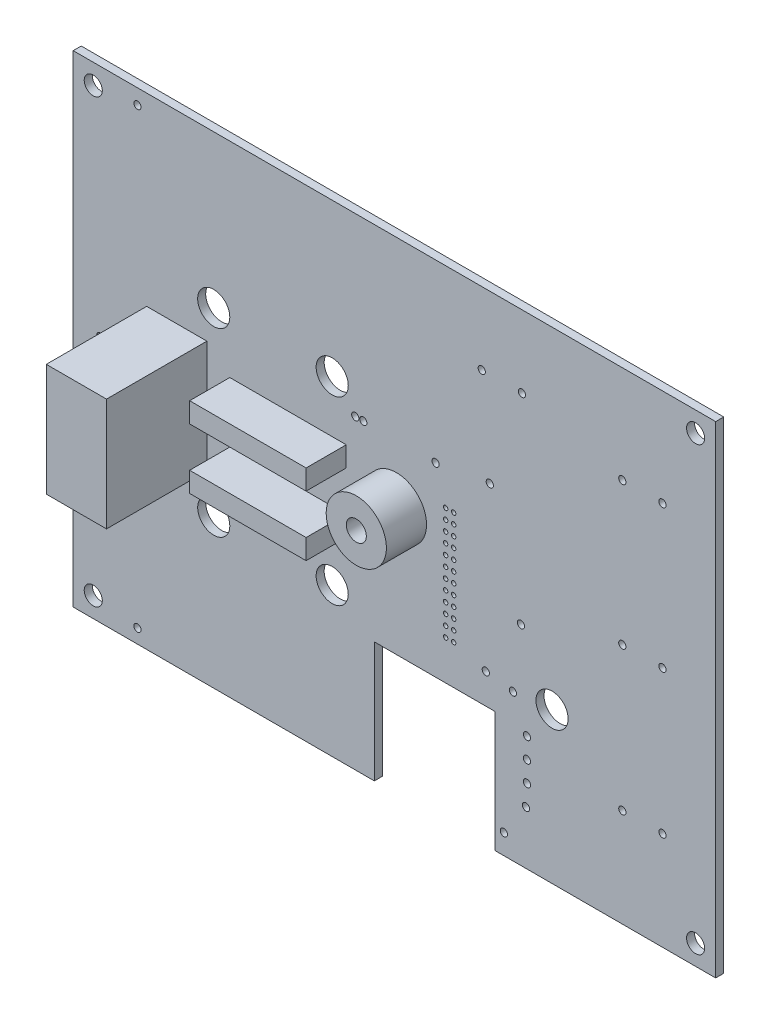
SolidWorks part; units mm, degrees
ref_plane "Спереди" through (0, 0, 0) normal (0, 0, 1) x (1, 0, 0)
ref_plane "Сверху" through (0, 0, 0) normal (0, 1, 0) x (1, 0, 0)
ref_plane "Справа" through (0, 0, 0) normal (1, 0, 0) x (0, 0, -1)
sketch "Эскиз1" plane through (0, 0, 0) normal (0, 0, 1) x (1, 0, 0)
  line L0 (-85.9912, 0) -> (95.9902, 0) construction
  line L2 (10, -60) -> (65, -60)
  line L3 (-95, -60) -> (-20, -60)
  line L4 (-95, -60) -> (-95, 60)
  line L5 (-95, 60) -> (65, 60)
  line L6 (65, -60) -> (65, 60)
  line L7 (-60, 22) -> (-60, -23) construction
  line L8 (-20, -60) -> (-20, -30)
  line L9 (-20, -30) -> (10, -30)
  line L10 (10, -60) -> (10, -30)
  line L11 (-60, 22) -> (-30.5, 22) construction
  line L12 (-60, -23) -> (-30.5, -23) construction
  circle A0 centre (-90, 55) radius 2.25
  circle A1 centre (60, 55) radius 2.25
  circle A2 centre (60, -55) radius 2.25
  circle A3 centre (-90, -55) radius 2.25
  circle A4 centre (-60, 22) radius 4
  circle A5 centre (-30.5, 22) radius 4
  circle A6 centre (-30.5, -23) radius 4
  circle A7 centre (-60, -23) radius 4
  circle A8 centre (24.25, -22.5) radius 4
  dimension "D4" = 5
  dimension "D5" = 4.5
  dimension "D14" = 8
  dimension "D15" = 5
  dimension "D16" = 119.25
  dimension "D17" = 37.5
  dimension "D21" = 45
  dimension "D6" = 29.5
  dimension "D10" = 29.5
  dimension "D11" = 4.5
  dimension "D13" = 5
  dimension "D18" = 75
  dimension "D1" = 160
  dimension "D2" = 120
  dimension "D3" = 5
  dimension "D7" = 35
  dimension "D8" = 37
  dimension "D9" = 37
  dimension "D12" = 82
  dimension "D23" = 30
extrude "Вытянуть1" add sketch "Эскиз1" along normal blind 2
sketch "Эскиз3" plane through (0, 0, 2) normal (0, 0, 1) x (1, 0, 0)
  line L0 (-95, -60) -> (-20, -60) construction
  line L1 (-95, 60) -> (-95, -60) construction
  circle A0 centre (-2.25, 7.75) radius 0.55
  dimension "D1" = 1.1
  dimension "D2" = 67.75
  dimension "D3" = 92.75
extrude "Вырез-Вытянуть1" cut sketch "Эскиз3" against normal blind 2
pattern_linear "Линейный массив1" count 2 spacing 2 along (1, 0, 0) count 12 spacing 2.54 along (0, -1, 0) of "Вырез-Вытянуть1"
sketch "Эскиз4" plane through (0, 0, 2) normal (0, 0, 1) x (1, 0, 0)
  line L0 (-95, 60) -> (-95, -60) construction
  line L1 (-95, -60) -> (-20, -60) construction
  line L2 (18, -49.9178) -> (18, -25.2535) construction
  line L3 (-86.5411, -3.5) -> (-52.0883, -3.5) construction
  line L4 (-95, 60) -> (-95, -60) construction
  line L6 (-95, 60) -> (-95, -60) construction
  line L7 (-95, -60) -> (-20, -60) construction
  line L8 (-88.25, -3.5) -> (-88.25, 7.7009) construction
  line L9 (10, -60) -> (65, -60) construction
  line L10 (-24.75, 16.23) -> (0, 16.23) construction
  circle A0 centre (17.75, -46.75) radius 0.9
  circle A1 centre (-24.75, 16.23) radius 0.9
  circle A2 centre (-88.25, 1.58) radius 0.9
  circle A3 centre (18, -41.5) radius 0.9
  circle A4 centre (14.5, -23.5) radius 0.9
  circle A5 centre (18, -36.42) radius 0.9
  circle A6 centre (-22.75, 16.23) radius 0.9
  circle A7 centre (-4.75, 16.23) radius 0.9
  circle A9 centre (18, -31.34) radius 0.9
  circle A12 centre (-88.25, -3.5) radius 0.9
  dimension "D3" = 112.75
  dimension "D6" = 36.5
  dimension "D7" = 109.5
  dimension "D8" = 72.25
  dimension "D9" = 76.23
  dimension "D10" = 70.25
  dimension "D11" = 5.08
  dimension "D14" = 1.8
  dimension "D15" = 90.25
  dimension "D18" = 5.08
  dimension "D16" = 1.8
  dimension "D17" = 5.08
  dimension "D2" = 113
  dimension "D4" = 13.25
  dimension "D5" = 18.5
  dimension "D12" = 56.5
  dimension "D13" = 6.75
extrude "Вырез-Вытянуть2" cut sketch "Эскиз4" against normal blind 2
sketch "Эскиз5" plane through (0, 0, 2) normal (0, 0, 1) x (1, 0, 0)
  line L0 (41.75, 35.75) -> (41.75, -46.6763) construction
  line L2 (41.75, 35.75) -> (51.75, 35.75) construction
  line L3 (41.75, -35.5) -> (51.75, -35.5) construction
  line L4 (-95, -60) -> (-20, -60) construction
  line L5 (41.75, 0.25) -> (51.75, 0.25) construction
  line L6 (10, -60) -> (65, -60) construction
  line L7 (-95, 60) -> (-95, -60) construction
  line L8 (10, -60) -> (65, -60) construction
  line L9 (-95, -60) -> (-20, -60) construction
  line L12 (-95, 60) -> (-95, -60) construction
  line L16 (6.75, 42) -> (16.75, 42) construction
  line L17 (10, -60) -> (65, -60) construction
  circle A0 centre (41.75, 35.75) radius 0.9
  circle A1 centre (51.75, 35.75) radius 0.9
  circle A2 centre (6.75, 42) radius 0.9
  circle A3 centre (16.75, 42) radius 0.9
  circle A4 centre (41.75, -35.5) radius 0.9
  circle A5 centre (51.75, -35.5) radius 0.9
  circle A6 centre (41.75, 0.25) radius 0.9
  circle A7 centre (51.75, 0.25) radius 0.9
  circle A8 centre (12.25, -55) radius 0.9
  circle A9 centre (-79, 56.25) radius 0.9
  circle A10 centre (-79, -56.5) radius 0.9
  circle A11 centre (8.75, 18.5) radius 0.9
  circle A12 centre (16.5, -8) radius 0.9
  circle A13 centre (7.75, -22.5) radius 0.9
  dimension "D1" = 10
  dimension "D2" = 1.8
  dimension "D3" = 102
  dimension "D4" = 136.75
  dimension "D5" = 95.75
  dimension "D6" = 78.5
  dimension "D7" = 10
  dimension "D8" = 101.75
  dimension "D11" = 103.75
  dimension "D12" = 5
  dimension "D13" = 60.25
  dimension "D19" = 52
  dimension "D9" = 10
  dimension "D10" = 24.5
  dimension "D14" = 10
  dimension "D15" = 107.25
  dimension "D16" = 16
  dimension "D17" = 3.5
  dimension "D18" = 16
  dimension "D20" = 111.5
  dimension "D21" = 37.5
  dimension "D22" = 102.75
extrude "Вырез-Вытянуть3" cut sketch "Эскиз5" against normal blind 10
sketch "Эскиз6" plane through (0, 0, 2) normal (0, 0, 1) x (1, 0, 0)
  line L0 (-95, -60) -> (-20, -60) construction
  line L1 (-76.7, -14) -> (-61.7, -14)
  line L2 (-76.7, -14) -> (-76.7, 14)
  line L3 (-76.7, 14) -> (-61.7, 14)
  line L4 (-61.7, -14) -> (-61.7, 14)
  line L5 (-56, 4) -> (-27, 4)
  line L6 (-56, 4) -> (-56, 9)
  line L7 (-56, 9) -> (-27, 9)
  line L8 (-27, 4) -> (-27, 9)
  line L9 (-56, -11) -> (-27, -11)
  line L10 (-56, -11) -> (-56, -6)
  line L11 (-56, -6) -> (-27, -6)
  line L12 (-27, -11) -> (-27, -6)
  line L14 (-95, 60) -> (-95, -60) construction
  circle A0 centre (-14.5, 1.75) radius 2.5
  circle A1 centre (-14.5, 1.75) radius 7.5
  dimension "D1" = 15
  dimension "D2" = 5
  dimension "D3" = 15
  dimension "D4" = 28
  dimension "D5" = 18.3
  dimension "D6" = 5
  dimension "D7" = 5
  dimension "D8" = 29
  dimension "D9" = 39
  dimension "D10" = 69
  dimension "D11" = 49
  dimension "D12" = 46
  dimension "D13" = 80.5
  dimension "D14" = 61.75
  dimension "D15" = 29
  dimension "D16" = 39
extrude "Вытянуть2" add sketch "Эскиз6" along normal blind 10
sketch "Эскиз7" plane through (0, 0, 12) normal (0, 0, 1) x (1, 0, 0)
  line L4 (-76.7, 14) -> (-76.7, -14)
  line L5 (-76.7, -14) -> (-61.7, -14)
  line L6 (-61.7, -14) -> (-61.7, 14)
  line L7 (-61.7, 14) -> (-76.7, 14)
  line L8 (-76.7, 14) -> (-76.7, -14)
  line L9 (-76.7, -14) -> (-61.7, -14)
  line L10 (-61.7, -14) -> (-61.7, 14)
  line L11 (-61.7, 14) -> (-76.7, 14)
  dimension "D1" = 0
extrude "Вытянуть3" add sketch "Эскиз7" along normal blind 15
sketch "Эскиз8" plane through (0, 0, 2) normal (0, 0, 1) x (1, 0, 0)
  line L0 (-95, -60) -> (-20, -60) construction
  line L1 (-95, 60) -> (-95, -60) construction
  circle A0 centre (-8.5, -18) radius 2.5
  dimension "D1" = 5
  dimension "D2" = 42
  dimension "D3" = 86.5
extrude "Вытянуть4" add sketch "Эскиз8" against normal blind 15.5
sketch "Эскиз9" plane through (0, 0, 0) normal (0, 0, -1) x (-1, 0, 0)
  circle A0 centre (8.5, -18) radius 3
  dimension "D1" = 6
extrude "Вытянуть5" add sketch "Эскиз9" along normal blind 5
sketch "Эскиз10" plane through (0, 0, 0) normal (0, 0, 1) x (1, 0, 0)
  line L0 (-8.5, -18) -> (-8.5, -13.7914) construction
  line L1 (-11.3261, -18) -> (-4.2016, -18) construction
  circle A0 centre (-8.5, -16.4963) radius 0.3
  circle A2 centre (-8.5, -18) radius 3
  circle A3 centre (-9.77, -19.0363) radius 0.3
  circle A4 centre (-7.23, -19.0363) radius 0.3
  dimension "D2" = 2.54
  dimension "D3" = 2.54
  dimension "D4" = 0.6
extrude "Вырез-Вытянуть4" cut sketch "Эскиз10" against normal blind 4.5
chamfer "Фаска1" distance 0.5 angle 45 1 edges at (-6, -18, -13.5)
